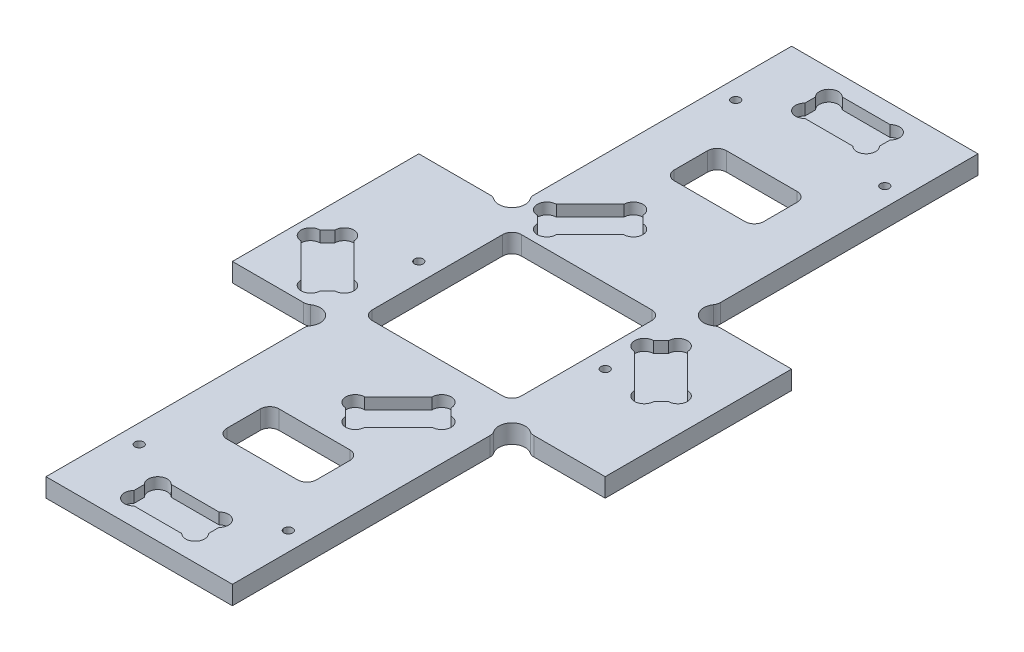
SolidWorks part; units mm, degrees
ref_plane "Front" through (0, 0, 0) normal (0, 0, 1) x (1, 0, 0)
ref_plane "Top" through (0, 0, 0) normal (0, 1, 0) x (1, 0, 0)
ref_plane "Right" through (0, 0, 0) normal (1, 0, 0) x (0, 0, -1)
sketch "Sketch1" plane through (0, 0, 0) normal (0, 1, 0) x (1, 0, 0)
  line L0 (45.4057, 247.3952) -> (45.4057, -6.6048) construction
  line L1 (13.6557, -6.6048) -> (77.1557, -6.6048)
  line L2 (13.6557, -6.6048) -> (13.6557, 247.3952)
  line L3 (13.6557, 247.3952) -> (77.1557, 247.3952)
  line L4 (77.1557, -6.6048) -> (77.1557, 247.3952)
  line L5 (13.6557, 152.1452) -> (-18.0943, 152.1452)
  line L6 (13.6557, 152.1452) -> (13.6557, 88.6452)
  line L7 (13.6557, 88.6452) -> (-18.0943, 88.6452)
  line L8 (-18.0943, 152.1452) -> (-18.0943, 88.6452)
  line L9 (77.1557, 88.6452) -> (108.9057, 88.6452)
  line L10 (108.9057, 152.1452) -> (108.9057, 88.6452)
  line L11 (77.1557, 152.1452) -> (108.9057, 152.1452)
  line L12 (77.1557, 152.1452) -> (77.1557, 88.6452)
  dimension "D1" = 63.5
  dimension "D2" = 254
  dimension "D3" = 31.75
  dimension "D4" = 63.5
  dimension "D5" = 95.25
extrude "Boss-Extrude1" add sketch "Sketch1" along normal blind 6.35 contours L5 L8 L7 L2 | L0 L3 L2 L1 | L3 L0 L1 L4 | L11 L4 L9 L10
sketch "Sketch2" plane through (0, 6.35, 0) normal (0, 1, 0) x (1, 0, 0)
  line L0 (13.6557, 88.6452) -> (77.1557, 152.1452) construction
  line L1 (77.1557, 152.1452) -> (77.1557, 88.6452) construction
  line L2 (77.1557, 88.6452) -> (45.4057, 120.3952) construction
  line L3 (45.4057, 120.3952) -> (45.4057, 152.1452) construction
  line L4 (45.4057, 152.1452) -> (13.6557, 152.1452) construction
  line L5 (13.6557, 152.1452) -> (45.4057, 120.3952) construction
  line L6 (2.3005, 109.6188) -> (-6.6798, 100.6386) construction
  line L7 (11.2807, 100.6386) -> (-6.6798, 118.5991)
  line L8 (-6.6798, 118.5991) -> (11.2807, 100.6386)
  line L9 (-6.6798, 118.5991) -> (-15.6601, 109.6188)
  line L10 (11.2807, 100.6386) -> (2.3005, 91.6583)
  line L11 (-15.6601, 109.6188) -> (2.3005, 91.6583)
  line L23 (11.2807, 100.6386) -> (2.3005, 91.6583)
  line L28 (43.9231, 166.4458) -> (25.9626, 148.4853)
  line L29 (43.9231, 166.4458) -> (34.9428, 175.4261)
  line L30 (34.9428, 175.4261) -> (16.9823, 157.4655)
  line L31 (25.9626, 148.4853) -> (16.9823, 157.4655)
  line L36 (43.9231, 166.4458) -> (34.9428, 175.4261)
  line L38 (6.7906, 96.1485) -> (-11.1699, 114.109) construction
  line L43 (91.7698, 115.8429) -> (73.8093, 133.8034)
  line L44 (91.7698, 115.8429) -> (100.7501, 124.8232)
  line L45 (100.7501, 124.8232) -> (82.7895, 142.7837)
  line L46 (73.8093, 133.8034) -> (82.7895, 142.7837)
  line L51 (91.7698, 115.8429) -> (100.7501, 124.8232)
  line L58 (41.1669, 67.9962) -> (59.1274, 85.9567)
  line L59 (41.1669, 67.9962) -> (50.1472, 59.0159)
  line L60 (50.1472, 59.0159) -> (68.1077, 76.9765)
  line L61 (59.1274, 85.9567) -> (68.1077, 76.9765)
  line L66 (41.1669, 67.9962) -> (50.1472, 59.0159)
  point P15 (2.3005, 109.6188)
  point P64 (42.545, 117.221)
  dimension "D1" = 22.86
  dimension "D2" = 25.4
  dimension "D3" = 12.7
  dimension "D7" = 38.1
  dimension "D6" = 4
extrude "Cut-Extrude14" cut sketch "Sketch2" against normal blind 3.81 contours L9 L11 L10 L7 | L31 L28 L29 L30 | L46 L43 L44 L45 | L61 L58 L59 L60
sketch "Sketch14" plane through (0, 6.35, 0) normal (0, 1, 0) x (1, 0, 0)
  line L0 (45.4057, -6.6048) -> (45.4057, 247.3952) construction
  line L1 (13.6557, -6.6048) -> (77.1557, -6.6048) construction
  line L2 (13.6557, 247.3952) -> (77.1557, 247.3952) construction
  line L3 (-18.0943, 120.3952) -> (108.9057, 120.3952) construction
  line L4 (32.7057, 241.0452) -> (58.1057, 241.0452)
  line L5 (32.7057, 241.0452) -> (32.7057, 228.3452)
  line L6 (32.7057, 228.3452) -> (58.1057, 228.3452)
  line L7 (58.1057, 241.0452) -> (58.1057, 228.3452)
  line L8 (32.7057, 241.0452) -> (58.1057, 228.3452) construction
  line L9 (32.7057, 228.3452) -> (58.1057, 241.0452) construction
  line L10 (-18.0943, 152.1452) -> (-18.0943, 88.6452) construction
  line L11 (108.9057, 152.1452) -> (108.9057, 88.6452) construction
  line L12 (32.7057, 12.4452) -> (58.1057, 12.4452)
  line L13 (58.1057, -0.2548) -> (58.1057, 12.4452)
  line L14 (32.7057, -0.2548) -> (58.1057, -0.2548)
  line L15 (32.7057, -0.2548) -> (32.7057, 12.4452)
  point P6 (45.4057, 234.6952)
  dimension "D1" = 12.7
  dimension "D2" = 25.4
  dimension "D3" = 6.35
extrude "Cut-Extrude16" cut sketch "Sketch14" against normal blind 3.81
sketch "Sketch15" plane through (0, 6.35, 0) normal (0, 1, 0) x (1, 0, 0)
  line L0 (45.4057, 247.3952) -> (45.4057, -6.6048) construction
  line L1 (13.6557, 247.3952) -> (77.1557, 247.3952) construction
  line L2 (13.6557, -6.6048) -> (77.1557, -6.6048) construction
  line L3 (45.4057, -6.6048) -> (108.9057, 120.3952) construction
  line L4 (108.9057, 152.1452) -> (108.9057, 88.6452) construction
  line L5 (108.9057, 120.3952) -> (-18.0943, 120.3952) construction
  line L6 (-18.0943, 152.1452) -> (-18.0943, 88.6452) construction
  line L7 (30.1657, 35.3052) -> (60.6457, 35.3052)
  line L8 (20.0057, 94.9952) -> (70.8057, 94.9952)
  line L9 (20.0057, 94.9952) -> (20.0057, 145.7952)
  line L10 (20.0057, 145.7952) -> (70.8057, 145.7952)
  line L11 (70.8057, 94.9952) -> (70.8057, 145.7952)
  line L12 (20.0057, 94.9952) -> (70.8057, 145.7952) construction
  line L13 (20.0057, 145.7952) -> (70.8057, 94.9952) construction
  line L14 (30.1657, 187.7052) -> (60.6457, 187.7052)
  line L15 (30.1657, 187.7052) -> (30.1657, 205.4852)
  line L16 (30.1657, 205.4852) -> (60.6457, 205.4852)
  line L17 (60.6457, 187.7052) -> (60.6457, 205.4852)
  line L18 (30.1657, 187.7052) -> (60.6457, 205.4852) construction
  line L19 (30.1657, 205.4852) -> (60.6457, 187.7052) construction
  line L20 (60.6457, 53.0852) -> (60.6457, 35.3052)
  line L21 (30.1657, 53.0852) -> (60.6457, 53.0852)
  line L22 (30.1657, 53.0852) -> (30.1657, 35.3052)
  point P6 (45.4057, 120.3952)
  point P17 (45.4057, 196.5952)
  dimension "D1" = 50.8
  dimension "D2" = 50.8
  dimension "D3" = 17.78
  dimension "D4" = 30.48
  dimension "D5" = 50.8
extrude "Cut-Extrude17" cut sketch "Sketch15" against normal through all
fillet "Fillet1" radius 3.175 12 edges at (30.1657, 3.175, -205.4852) (30.1657, 3.175, -187.7052) (60.6457, 3.175, -187.7052) (60.6457, 3.175, -205.4852) (60.6457, 3.175, -53.0852) (30.1657, 3.175, -53.0852) (30.1657, 3.175, -35.3052) (60.6457, 3.175, -35.3052) (70.8057, 3.175, -94.9952) (70.8057, 3.175, -145.7952) (20.0057, 3.175, -145.7952) (20.0057, 3.175, -94.9952)
sketch "Sketch16" plane through (0, 6.35, 0) normal (0, 1, 0) x (1, 0, 0)
  line L0 (45.4057, -6.6048) -> (45.4057, 247.3952) construction
  line L1 (13.6557, 88.6452) -> (10.4807, 88.6452)
  line L2 (13.6557, 88.6452) -> (13.6557, 85.4702)
  line L3 (13.6557, 85.4702) -> (10.4807, 85.4702)
  line L4 (10.4807, 88.6452) -> (10.4807, 85.4702)
  line L5 (13.6557, -6.6048) -> (77.1557, -6.6048) construction
  line L6 (13.6557, 247.3952) -> (77.1557, 247.3952) construction
  line L7 (45.4057, 247.3952) -> (108.9057, 120.3952) construction
  line L8 (108.9057, 152.1452) -> (108.9057, 88.6452) construction
  line L9 (108.9057, 120.3952) -> (-18.0943, 120.3952) construction
  line L10 (-18.0943, 152.1452) -> (-18.0943, 88.6452) construction
  line L11 (77.1557, 85.4702) -> (80.3307, 85.4702)
  line L12 (80.3307, 88.6452) -> (80.3307, 85.4702)
  line L13 (77.1557, 88.6452) -> (80.3307, 88.6452)
  line L14 (77.1557, 88.6452) -> (77.1557, 85.4702)
  line L16 (77.1557, 152.1452) -> (77.1557, 155.3202)
  line L17 (77.1557, 152.1452) -> (80.3307, 152.1452)
  line L18 (80.3307, 152.1452) -> (80.3307, 155.3202)
  line L19 (77.1557, 155.3202) -> (80.3307, 155.3202)
  line L20 (13.6557, 155.3202) -> (10.4807, 155.3202)
  line L21 (10.4807, 152.1452) -> (10.4807, 155.3202)
  line L22 (13.6557, 152.1452) -> (10.4807, 152.1452)
  line L23 (13.6557, 152.1452) -> (13.6557, 155.3202)
  circle A0 centre (10.4807, 85.4702) radius 4.4901
  circle A1 centre (80.3307, 85.4702) radius 4.4901
  circle A2 centre (80.3307, 155.3202) radius 4.4901
  circle A3 centre (10.4807, 155.3202) radius 4.4901
  dimension "D1" = 3.175
  dimension "D2" = 3.175
extrude "Cut-Extrude18" cut sketch "Sketch16" against normal through all contours L1 A0 L2 L3 L4 | L1 L4 L3 L2 | L13 L14 L11 L12 | L14 A1 L13 L12 L11 | L19 L16 L17 L18 | L17 A2 L16 L19 L18 | L22 L23 L20 L21 | L23 A3 L22 L21 L20
fillet "Fillet2" radius 3.175 8 edges at (13.6557, 3.175, -158.4952) (7.3057, 3.175, -152.1452) (77.1557, 3.175, -158.4952) (83.5057, 3.175, -152.1452) (77.1557, 3.175, -82.2952) (83.5057, 3.175, -88.6452) (13.6557, 3.175, -82.2952) (7.3057, 3.175, -88.6452)
sketch "Sketch17" plane through (0, 6.35, 0) normal (0, 1, 0) x (1, 0, 0)
  line L0 (45.4057, -6.6048) -> (45.4057, 247.3952) construction
  line L1 (13.6557, -6.6048) -> (77.1557, -6.6048) construction
  line L2 (13.6557, 247.3952) -> (77.1557, 247.3952) construction
  line L3 (45.4057, 247.3952) -> (108.9057, 120.3952) construction
  line L4 (108.9057, 152.1452) -> (108.9057, 88.6452) construction
  line L5 (108.9057, 120.3952) -> (-18.0943, 120.3952) construction
  line L6 (-18.0943, 152.1452) -> (-18.0943, 88.6452) construction
  line L7 (-18.0943, 120.3952) -> (32.7057, 6.0952) construction
  line L8 (32.7057, 12.4452) -> (32.7057, -0.2548) construction
  line L9 (32.7057, 6.0952) -> (58.1057, 6.0952) construction
  line L10 (58.1057, -0.2548) -> (58.1057, 12.4452) construction
  line L11 (32.7057, 12.4452) -> (34.9917, 12.4452)
  line L12 (32.7057, 12.4452) -> (32.7057, 10.1592)
  line L13 (34.9917, 12.4452) -> (34.9917, 10.1592)
  line L14 (32.7057, 10.1592) -> (34.9917, 10.1592)
  line L15 (58.1057, 12.4452) -> (32.7057, 12.4452) construction
  line L16 (34.9917, -0.2548) -> (34.9917, 2.0312)
  line L17 (32.7057, 2.0312) -> (34.9917, 2.0312)
  line L18 (32.7057, -0.2548) -> (32.7057, 2.0312)
  line L19 (32.7057, -0.2548) -> (34.9917, -0.2548)
  line L20 (58.1057, -0.2548) -> (55.8197, -0.2548)
  line L21 (58.1057, -0.2548) -> (58.1057, 2.0312)
  line L22 (58.1057, 2.0312) -> (55.8197, 2.0312)
  line L23 (55.8197, -0.2548) -> (55.8197, 2.0312)
  line L24 (55.8197, 12.4452) -> (55.8197, 10.1592)
  line L25 (58.1057, 10.1592) -> (55.8197, 10.1592)
  line L26 (58.1057, 12.4452) -> (58.1057, 10.1592)
  line L27 (58.1057, 12.4452) -> (55.8197, 12.4452)
  line L28 (58.1057, 241.0452) -> (58.1057, 238.7592)
  line L29 (58.1057, 238.7592) -> (55.8197, 238.7592)
  line L30 (55.8197, 241.0452) -> (55.8197, 238.7592)
  line L31 (58.1057, 241.0452) -> (55.8197, 241.0452)
  line L32 (58.1057, 228.3452) -> (55.8197, 228.3452)
  line L33 (58.1057, 228.3452) -> (58.1057, 230.6312)
  line L34 (58.1057, 230.6312) -> (55.8197, 230.6312)
  line L35 (55.8197, 228.3452) -> (55.8197, 230.6312)
  line L36 (34.9917, 228.3452) -> (34.9917, 230.6312)
  line L37 (32.7057, 230.6312) -> (34.9917, 230.6312)
  line L38 (32.7057, 228.3452) -> (32.7057, 230.6312)
  line L39 (32.7057, 228.3452) -> (34.9917, 228.3452)
  line L40 (32.7057, 241.0452) -> (34.9917, 241.0452)
  line L41 (32.7057, 241.0452) -> (32.7057, 238.7592)
  line L42 (32.7057, 238.7592) -> (34.9917, 238.7592)
  line L43 (34.9917, 241.0452) -> (34.9917, 238.7592)
  circle A0 centre (34.9917, 10.1592) radius 3.2329
  circle A1 centre (34.9917, 2.0312) radius 3.2329
  circle A2 centre (55.8197, 2.0312) radius 3.2329
  circle A3 centre (55.8197, 10.1592) radius 3.2329
  circle A4 centre (55.8197, 238.7592) radius 3.2329
  circle A5 centre (55.8197, 230.6312) radius 3.2329
  circle A6 centre (34.9917, 230.6312) radius 3.2329
  circle A7 centre (34.9917, 238.7592) radius 3.2329
  dimension "D1" = 2.286
  dimension "D2" = 2.286
extrude "Cut-Extrude19" cut sketch "Sketch17" against normal blind 3.81 contours L43 L40 L41 L42 | L41 A7 L40 L43 L42 | L31 A4 L28 L29 L30 | L28 L31 L30 L29 | L33 A5 L32 L35 L34 | L35 L32 L33 L34 | L39 A6 L38 L37 L36 | L38 L39 L36 L37 | L19 A1 L18 L17 L16 | L18 L19 L16 L17 | L12 A0 L11 L13 L14 | L12 L14 L13 L11 | L27 A3 L26 L25 L24 | L26 L27 L24 L25 | L21 A2 L20 L23 L22 | L23 L20 L21 L22
sketch "Sketch18" plane through (0, 6.35, 0) normal (0, 1, 0) x (1, 0, 0)
  line L0 (-15.6601, 109.6188) -> (-14.0436, 111.2353)
  line L1 (-15.6601, 109.6188) -> (-14.0436, 108.0024)
  line L2 (-14.0436, 111.2353) -> (-12.4272, 109.6188)
  line L3 (-14.0436, 108.0024) -> (-12.4272, 109.6188)
  line L4 (-6.6798, 118.5991) -> (-15.6601, 109.6188) construction
  line L5 (-11.1699, 114.109) -> (6.7906, 96.1485) construction
  line L6 (11.2807, 100.6386) -> (2.3005, 91.6583) construction
  line L7 (6.7906, 96.1485) -> (2.3005, 109.6188) construction
  line L8 (11.2807, 100.6386) -> (-6.6798, 118.5991) construction
  line L9 (2.3005, 109.6188) -> (-6.6798, 100.6386) construction
  line L10 (-15.6601, 109.6188) -> (2.3005, 91.6583) construction
  line L11 (-8.2962, 116.9827) -> (-6.6798, 115.3662)
  line L12 (-5.0634, 116.9827) -> (-6.6798, 115.3662)
  line L13 (-6.6798, 118.5991) -> (-5.0634, 116.9827)
  line L14 (-6.6798, 118.5991) -> (-8.2962, 116.9827)
  line L15 (11.2807, 100.6386) -> (9.6643, 99.0221)
  line L16 (11.2807, 100.6386) -> (9.6643, 102.255)
  line L17 (9.6643, 102.255) -> (8.0478, 100.6386)
  line L18 (9.6643, 99.0221) -> (8.0478, 100.6386)
  line L19 (3.9169, 93.2748) -> (2.3005, 94.8912)
  line L20 (0.684, 93.2748) -> (2.3005, 94.8912)
  line L21 (2.3005, 91.6583) -> (0.684, 93.2748)
  line L22 (2.3005, 91.6583) -> (3.9169, 93.2748)
  line L23 (45.4057, 145.7952) -> (45.4057, 94.9952) construction
  line L24 (67.6307, 145.7952) -> (23.1807, 145.7952) construction
  line L25 (23.1807, 94.9952) -> (67.6307, 94.9952) construction
  line L26 (45.4057, 94.9952) -> (70.8057, 120.3952) construction
  line L27 (70.8057, 98.1702) -> (70.8057, 142.6202) construction
  line L28 (70.8057, 120.3952) -> (20.0057, 120.3952) construction
  line L29 (20.0057, 142.6202) -> (20.0057, 98.1702) construction
  circle A0 centre (-12.4272, 109.6188) radius 3.2329
  circle A1 centre (-6.6798, 115.3662) radius 3.2329
  circle A2 centre (8.0478, 100.6386) radius 3.2329
  circle A3 centre (2.3005, 94.8912) radius 3.2329
  dimension "D1" = 2.286
  dimension "D2" = 2.286
extrude "Cut-Extrude20" cut sketch "Sketch18" against normal blind 3.81 contours L1 L3 L2 L0 | L1 A0 L0 L2 L3 | L13 L14 L11 L12 | L14 A1 L13 L12 L11 | L18 L15 L16 L17 | L16 A2 L15 L18 L17 | L21 L22 L19 L20 | L22 A3 L21 L20 L19
sketch "Sketch19" plane through (0, 6.35, 0) normal (0, 1, 0) x (1, 0, 0)
  line L0 (34.9428, 175.4261) -> (33.3264, 173.8096)
  line L1 (34.9428, 175.4261) -> (36.5593, 173.8096)
  line L2 (33.3264, 173.8096) -> (34.9428, 172.1932)
  line L3 (36.5593, 173.8096) -> (34.9428, 172.1932)
  line L4 (43.9231, 166.4458) -> (34.9428, 175.4261) construction
  line L5 (34.9428, 175.4261) -> (16.9823, 157.4655) construction
  line L6 (39.433, 170.9359) -> (21.4725, 152.9754) construction
  line L7 (25.9626, 148.4853) -> (16.9823, 157.4655) construction
  line L8 (25.9626, 166.4458) -> (34.9428, 157.4655) construction
  line L9 (43.9231, 166.4458) -> (25.9626, 148.4853) construction
  line L11 (42.3067, 164.8294) -> (40.6902, 166.4458)
  line L12 (42.3067, 168.0622) -> (40.6902, 166.4458)
  line L13 (43.9231, 166.4458) -> (42.3067, 168.0622)
  line L14 (43.9231, 166.4458) -> (42.3067, 164.8294)
  line L15 (25.9626, 148.4853) -> (27.579, 150.1017)
  line L16 (25.9626, 148.4853) -> (24.3461, 150.1017)
  line L17 (24.3461, 150.1017) -> (25.9626, 151.7182)
  line L18 (27.579, 150.1017) -> (25.9626, 151.7182)
  line L19 (18.5988, 159.082) -> (20.2152, 157.4655)
  line L20 (18.5988, 155.8491) -> (20.2152, 157.4655)
  line L21 (16.9823, 157.4655) -> (18.5988, 155.8491)
  line L22 (16.9823, 157.4655) -> (18.5988, 159.082)
  line L23 (82.7895, 142.7837) -> (81.1731, 141.1672)
  line L24 (82.7895, 142.7837) -> (84.406, 141.1672)
  line L25 (81.1731, 141.1672) -> (82.7895, 139.5508)
  line L26 (84.406, 141.1672) -> (82.7895, 139.5508)
  line L27 (73.8093, 133.8034) -> (82.7895, 142.7837) construction
  line L28 (78.2994, 138.2935) -> (96.2599, 120.333) construction
  line L29 (91.7698, 115.8429) -> (100.7501, 124.8232) construction
  line L30 (91.7698, 133.8034) -> (82.7895, 124.8232) construction
  line L34 (75.4257, 135.4199) -> (77.0422, 133.8034)
  line L35 (75.4257, 132.187) -> (77.0422, 133.8034)
  line L36 (73.8093, 133.8034) -> (75.4257, 132.187)
  line L37 (73.8093, 133.8034) -> (75.4257, 135.4199)
  line L38 (100.7501, 124.8232) -> (82.7895, 142.7837) construction
  line L39 (91.7698, 115.8429) -> (73.8093, 133.8034) construction
  line L40 (99.1336, 123.2067) -> (97.5172, 124.8232)
  line L41 (99.1336, 126.4396) -> (97.5172, 124.8232)
  line L42 (100.7501, 124.8232) -> (99.1336, 126.4396)
  line L43 (100.7501, 124.8232) -> (99.1336, 123.2067)
  line L44 (91.7698, 115.8429) -> (93.3862, 117.4593)
  line L45 (91.7698, 115.8429) -> (90.1534, 117.4593)
  line L46 (90.1534, 117.4593) -> (91.7698, 119.0758)
  line L47 (93.3862, 117.4593) -> (91.7698, 119.0758)
  line L48 (45.657, 63.5061) -> (63.6175, 81.4666) construction
  line L49 (41.1669, 67.9962) -> (50.1472, 59.0159) construction
  line L50 (59.1274, 85.9567) -> (68.1077, 76.9765) construction
  line L51 (50.1472, 76.9765) -> (59.1274, 67.9962) construction
  line L52 (41.1669, 67.9962) -> (59.1274, 85.9567) construction
  line L53 (50.1472, 59.0159) -> (68.1077, 76.9765) construction
  line L54 (41.1669, 67.9962) -> (42.7833, 69.6126)
  line L55 (41.1669, 67.9962) -> (42.7833, 66.3798)
  line L56 (42.7833, 69.6126) -> (44.3998, 67.9962)
  line L57 (42.7833, 66.3798) -> (44.3998, 67.9962)
  line L59 (51.7636, 60.6324) -> (50.1472, 62.2488)
  line L60 (48.5307, 60.6324) -> (50.1472, 62.2488)
  line L61 (50.1472, 59.0159) -> (48.5307, 60.6324)
  line L62 (50.1472, 59.0159) -> (51.7636, 60.6324)
  line L63 (68.1077, 76.9765) -> (66.4912, 75.36)
  line L64 (68.1077, 76.9765) -> (66.4912, 78.5929)
  line L65 (66.4912, 78.5929) -> (64.8748, 76.9765)
  line L66 (66.4912, 75.36) -> (64.8748, 76.9765)
  line L67 (57.511, 84.3403) -> (59.1274, 82.7238)
  line L68 (60.7439, 84.3403) -> (59.1274, 82.7238)
  line L69 (59.1274, 85.9567) -> (60.7439, 84.3403)
  line L70 (59.1274, 85.9567) -> (57.511, 84.3403)
  circle A0 centre (34.9428, 172.1932) radius 3.2329
  circle A1 centre (40.6902, 166.4458) radius 3.2329
  circle A2 centre (25.9626, 151.7182) radius 3.2329
  circle A3 centre (20.2152, 157.4655) radius 3.2329
  circle A4 centre (82.7895, 139.5508) radius 3.2329
  circle A5 centre (77.0422, 133.8034) radius 3.2329
  circle A6 centre (97.5172, 124.8232) radius 3.2329
  circle A7 centre (91.7698, 119.0758) radius 3.2329
  circle A8 centre (44.3998, 67.9962) radius 3.2329
  circle A9 centre (50.1472, 62.2488) radius 3.2329
  circle A10 centre (64.8748, 76.9765) radius 3.2329
  circle A11 centre (59.1274, 82.7238) radius 3.2329
  dimension "D1" = 2.286
  dimension "D2" = 2.286
  dimension "D3" = 2.286
  dimension "D4" = 2.286
  dimension "D5" = 2.286
  dimension "D6" = 2.286
extrude "Cut-Extrude22" cut sketch "Sketch19" against normal blind 3.81 contours L55 A8 L54 L56 L57 | L61 L62 L59 L60 | L62 A9 L61 L60 L59 | L69 L70 L67 L68 | L70 A11 L69 L68 L67 | L66 L63 L64 L65 | L64 A10 L63 L66 L65 | L44 L47 L46 L45 | L44 A7 L45 L46 L47 | L43 L42 L41 L40 | L42 A6 L43 L40 L41 | L26 L24 L23 L25 | L23 A4 L24 L26 L25 | L37 L36 L35 L34 | L36 A5 L37 L34 L35 | L15 A2 L16 L17 L18 | L15 L18 L17 L16 | L22 L21 L20 L19 | L21 A3 L22 L19 L20 | L3 L1 L0 L2 | L0 A0 L1 L3 L2 | L14 L13 L12 L11 | L13 A1 L14 L11 L12 | L55 L57 L56 L54
sketch "Sketch20" plane through (0, 6.35, 0) normal (0, 1, 0) x (1, 0, 0)
  line L0 (45.4057, 247.3952) -> (45.4057, -6.6048) construction
  line L1 (13.6557, 247.3952) -> (77.1557, 247.3952) construction
  line L2 (13.6557, -6.6048) -> (77.1557, -6.6048) construction
  line L3 (45.4057, -6.6048) -> (108.9057, 120.3952) construction
  line L4 (108.9057, 152.1452) -> (108.9057, 88.6452) construction
  line L5 (108.9057, 120.3952) -> (-18.0943, 120.3952) construction
  line L6 (-18.0943, 152.1452) -> (-18.0943, 88.6452) construction
  circle A0 centre (20.0057, 221.9952) radius 1.4732
  circle A1 centre (70.8057, 221.9952) radius 1.4732
  circle A2 centre (70.8057, 18.7952) radius 1.4732
  circle A3 centre (20.0057, 18.7952) radius 1.4732
  circle A4 centre (13.6557, 120.3952) radius 1.4732
  circle A5 centre (77.1557, 120.3952) radius 1.4732
  dimension "D1" = 2.9464
  dimension "D2" = 25.4
  dimension "D3" = 25.4
  dimension "D4" = 2.9464
  dimension "D5" = 31.75
extrude "Cut-Extrude23" cut sketch "Sketch20" against normal through all and the other way through all
